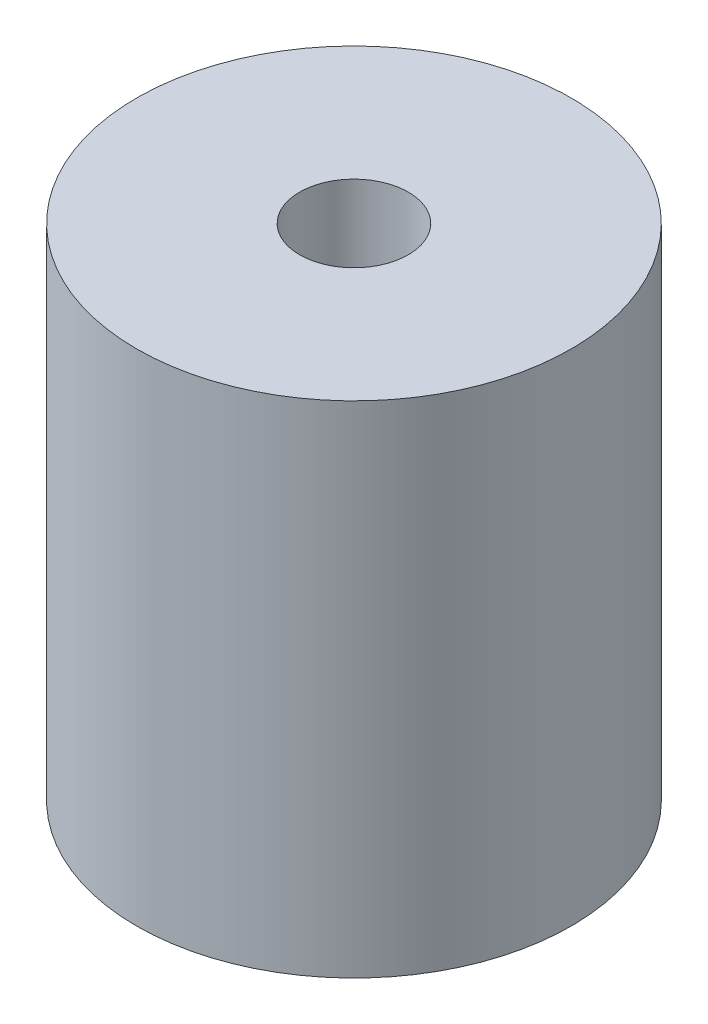
SolidWorks part; units mm, degrees
ref_plane "Alzado" through (0, 0, 0) normal (0, 0, 1) x (1, 0, 0)
ref_plane "Planta" through (0, 0, 0) normal (0, 1, 0) x (1, 0, 0)
ref_plane "Vista lateral" through (0, 0, 0) normal (1, 0, 0) x (0, 0, -1)
sketch "Croquis2" plane through (0, 0, 0) normal (0, 1, 0) x (1, 0, 0)
  circle A0 centre (0, 0) radius 2.5
  circle A1 centre (0, 0) radius 10
  dimension "D1" = 5
  dimension "D2" = 20
extrude "Saliente-Extruir1" add sketch "Croquis2" along normal blind 23
